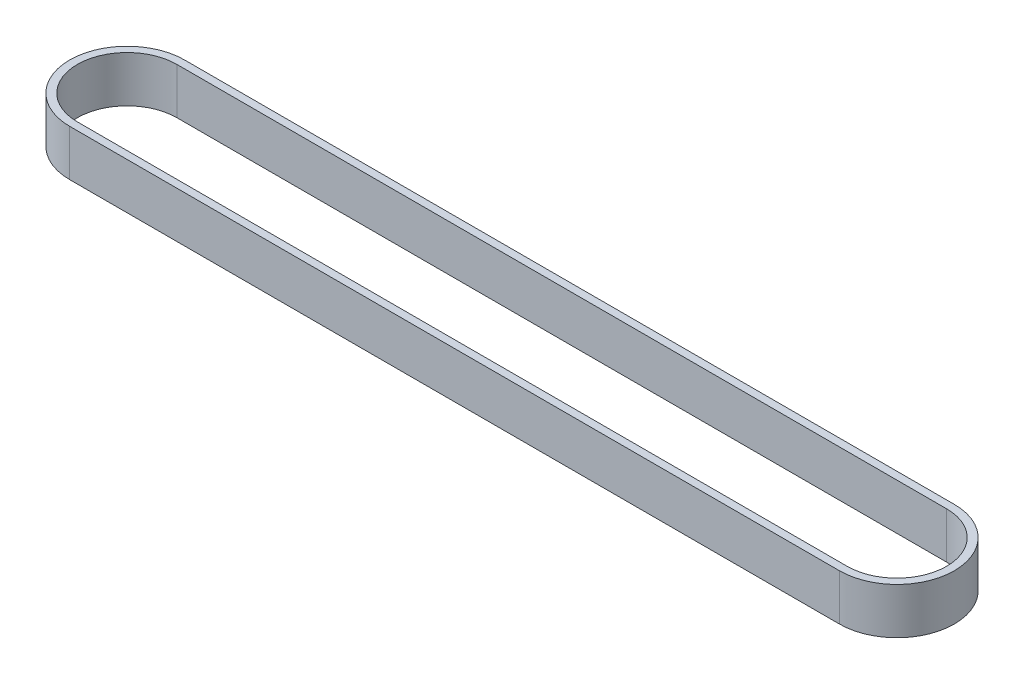
SolidWorks part; units mm, degrees
ref_plane "前视" through (0, 0, 0) normal (0, 0, 1) x (1, 0, 0)
ref_plane "上视" through (0, 0, 0) normal (0, 1, 0) x (1, 0, 0)
ref_plane "右视" through (0, 0, 0) normal (1, 0, 0) x (0, 0, -1)
sketch "草图1" plane through (0, 0, 0) normal (0, 1, 0) x (1, 0, 0)
  line L0 (-50, 7.465) -> (50, 7.465)
  line L1 (-50, 6.465) -> (50, 6.465)
  line L2 (-50, 6.465) -> (-50, -6.465) construction
  line L3 (-50, -6.465) -> (50, -6.465)
  line L4 (50, 6.465) -> (50, -6.465) construction
  line L5 (-50, 6.465) -> (50, -6.465) construction
  line L6 (-50, -6.465) -> (50, 6.465) construction
  line L7 (-50, -7.465) -> (50, -7.465)
  arc A0 (-50, 6.465) -> (-50, -6.465) centre (-50, 0) ccw
  arc A1 (50, -6.465) -> (50, 6.465) centre (50, 0) ccw
  arc A2 (50, -7.465) -> (50, 7.465) centre (50, 0) ccw
  arc A3 (-50, 7.465) -> (-50, -7.465) centre (-50, 0) ccw
  point P0 (0, 0)
  dimension "D1" = 12.93
  dimension "D2" = 100
  dimension "D3" = 1
extrude "凸台-拉伸1" add sketch "草图1" along normal blind 6
